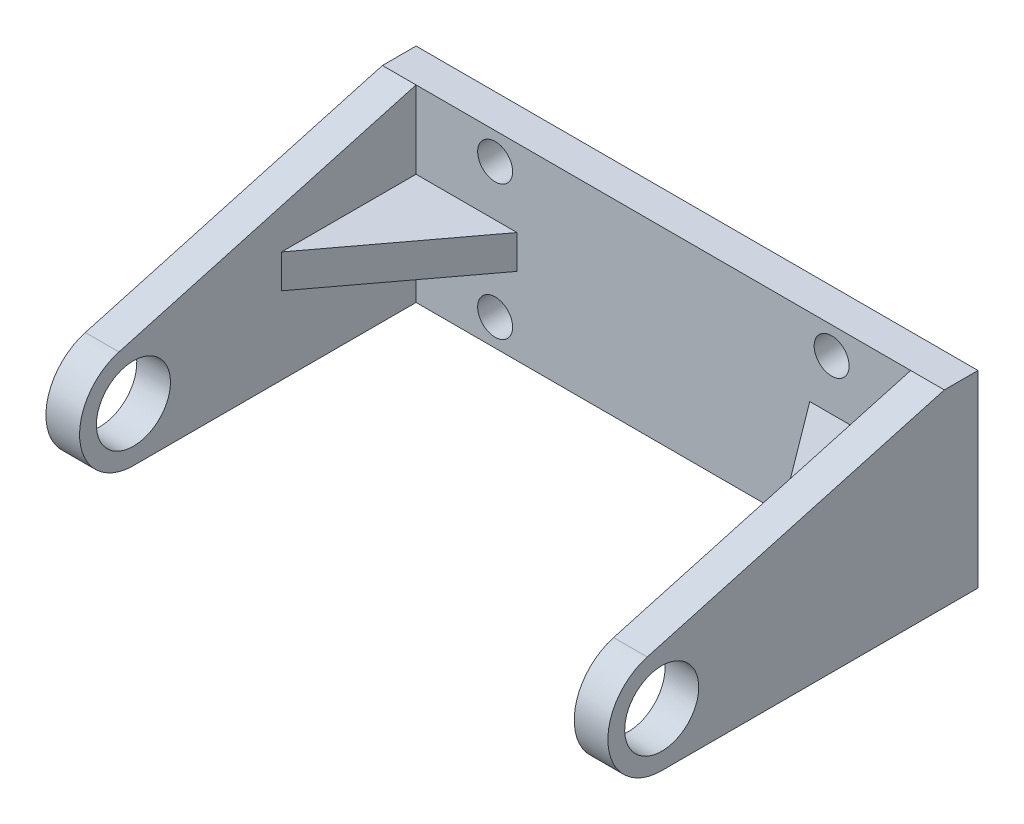
SolidWorks part; units mm, degrees
ref_plane "前视基准面" through (0, 0, 0) normal (0, 0, 1) x (1, 0, 0)
ref_plane "上视基准面" through (0, 0, 0) normal (0, 1, 0) x (1, 0, 0)
ref_plane "右视基准面" through (0, 0, 0) normal (1, 0, 0) x (0, 0, -1)
sketch "草图1" plane through (0, 0, 0) normal (0, 0, 1) x (1, 0, 0)
  line L1 (-41.75, 14) -> (41.75, 14)
  line L2 (-41.75, 14) -> (-41.75, -14)
  line L3 (-41.75, -14) -> (41.75, -14)
  line L4 (41.75, 14) -> (41.75, -14)
  line L5 (-41.75, 14) -> (41.75, -14) construction
  line L6 (-41.75, -14) -> (41.75, 14) construction
  point P0 (0, 0)
  dimension "D1" = 28
  dimension "D2" = 83.5
extrude "凸台-拉伸1" add sketch "草图1" along normal blind 5
sketch "草图2" plane through (-41.75, 0, 0) normal (-1, 0, 0) x (0, 0, 1)
  line L3 (5, 14) -> (5, -14)
  line L5 (5, -14) -> (47, -14)
  line L6 (5, 14) -> (49.1461, 1.7068)
  line L7 (5, 14) -> (0, 14) construction
  arc A0 (47, -14) -> (49.1461, 1.7068) centre (47, -6) ccw
  circle A1 centre (47, -6) radius 5.5
  point P7 (0, 0)
  point P9 (51.0608, -2.277)
  dimension "D2" = 11
  dimension "D1" = 42
  dimension "D3" = 20
extrude "凸台-拉伸2" add sketch "草图2" against normal blind 5
sketch "草图3" plane through (41.75, 0, 0) normal (1, 0, 0) x (0, 0, -1)
  line L3 (-5, 14) -> (-49.1461, 1.7068)
  line L4 (-47, -14) -> (-5, -14)
  line L5 (-5, -14) -> (-5, 14)
  line L6 (-5, 14) -> (-49.1461, 1.7068)
  line L7 (-47, -14) -> (-5, -14)
  line L8 (-5, -14) -> (-5, 14)
  circle A0 centre (-47, -6) radius 5.5 construction
  arc A1 (-49.1461, 1.7068) -> (-47, -14) centre (-47, -6) ccw
  arc A2 (-49.1461, 1.7068) -> (-47, -14) centre (-47, -6) ccw
  circle A3 centre (-47, -6) radius 5.5
  dimension "D1" = 0
extrude "凸台-拉伸3" add sketch "草图3" against normal blind 5
sketch "草图4" plane through (0, 0, 5) normal (0, 0, 1) x (1, 0, 0)
  line L1 (25, 10) -> (-25, 10) construction
  line L2 (25, 10) -> (25, -10) construction
  line L3 (25, -10) -> (-25, -10) construction
  line L4 (-25, 10) -> (-25, -10) construction
  line L5 (25, 10) -> (-25, -10) construction
  line L6 (25, -10) -> (-25, 10) construction
  circle A0 centre (-25, 10) radius 2.6
  circle A1 centre (25, 10) radius 2.6
  circle A2 centre (25, -10) radius 2.6
  circle A3 centre (-25, -10) radius 2.6
  point P0 (0, 0)
  dimension "D3" = 5.2
  dimension "D1" = 50
  dimension "D2" = 20
extrude "切除-拉伸2" cut sketch "草图4" against normal blind 5
sketch "草图5" plane through (0, 0, 0) normal (0, 1, 0) x (1, 0, 0)
  line L0 (-36.75, -5) -> (-21.75, -5)
  line L1 (36.75, -5) -> (-36.75, -5) construction
  line L2 (-21.75, -5) -> (-36.75, -25)
  line L3 (-36.75, -49.1461) -> (-36.75, -5) construction
  line L4 (-36.75, -25) -> (-36.75, -5)
  line L5 (36.75, -5) -> (36.75, -25.0855)
  line L6 (36.75, -5) -> (36.75, -49.1461) construction
  line L7 (36.75, -25.0855) -> (21.75, -5)
  line L8 (21.75, -5) -> (36.75, -5)
  dimension "D1" = 15
  dimension "D2" = 20
extrude "凸台-拉伸4" add sketch "草图5" along normal mid plane 5
